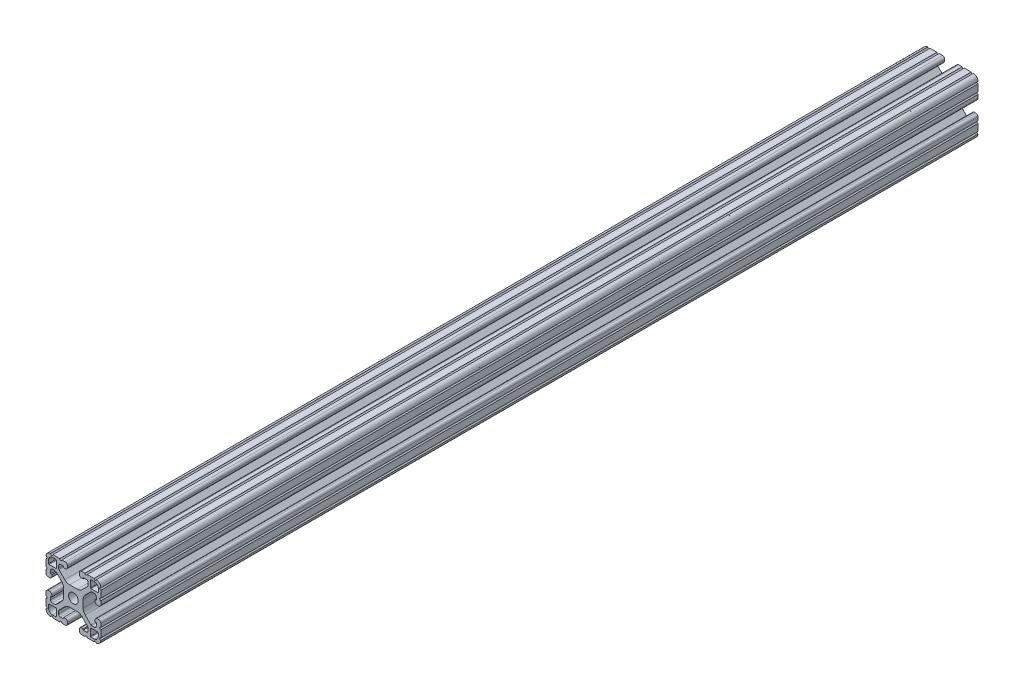
SolidWorks part; units mm, degrees
ref_plane "Front Plane" through (0, 0, 0) normal (0, 0, 1) x (1, 0, 0)
ref_plane "Top Plane" through (0, 0, 0) normal (0, 1, 0) x (1, 0, 0)
ref_plane "Right Plane" through (0, 0, 0) normal (1, 0, 0) x (0, 0, -1)
sketch "Sketch1" plane through (0, 0, 0) normal (0, 0, 1) x (1, 0, 0)
  line L0 (-10.0267, 12.1519) -> (-6.0215, 8.1473)
  line L1 (10.0267, -12.1519) -> (6.0215, -8.1473)
  line L2 (10.287, -14.5547) -> (10.287, -12.7802)
  line L3 (6.8141, -15.8247) -> (9.017, -15.8247)
  line L4 (-10.287, 14.5547) -> (-10.287, 12.7802)
  line L5 (6.8141, -14.986) -> (6.8141, -15.8247)
  line L6 (-6.8141, 15.8247) -> (-9.017, 15.8247)
  line L7 (2.6631, 6.7564) -> (-2.6631, 6.7564)
  line L8 (-6.8141, 14.986) -> (-6.8141, 15.8247)
  line L9 (-5.6388, 14.986) -> (-6.8141, 14.986)
  line L10 (-4.064, 17.4752) -> (-4.064, 16.5608)
  line L11 (-7.9756, 19.05) -> (-5.6388, 19.05)
  line L12 (-14.3256, 19.05) -> (-9.4996, 19.05)
  line L13 (-15.875, 19.05) -> (-15.8496, 19.05)
  line L14 (-19.05, 15.8496) -> (-19.05, 15.875)
  line L15 (-19.05, 9.4996) -> (-19.05, 14.3256)
  line L16 (-19.05, 5.6388) -> (-19.05, 7.9756)
  line L17 (5.6388, -14.986) -> (6.8141, -14.986)
  line L18 (4.064, -17.4752) -> (4.064, -16.5608)
  line L19 (7.9756, -19.05) -> (5.6388, -19.05)
  line L20 (-16.5608, 4.064) -> (-17.4752, 4.064)
  line L21 (14.3256, -19.05) -> (9.4996, -19.05)
  line L22 (-14.986, 6.7506) -> (-14.986, 5.6388)
  line L23 (-15.879, 6.7506) -> (-14.986, 6.7506)
  line L24 (15.875, -19.05) -> (15.8496, -19.05)
  line L25 (19.05, -15.8496) -> (19.05, -15.875)
  line L26 (-15.879, 8.9192) -> (-15.879, 6.7506)
  line L27 (-12.7428, 10.1892) -> (-14.609, 10.1892)
  line L28 (19.05, -9.4996) -> (19.05, -14.3256)
  line L29 (19.05, -5.6388) -> (19.05, -7.9756)
  line L30 (-8.1479, 5.9632) -> (-12.1142, 9.9289)
  line L31 (-16.891, 11.8618) -> (-12.2428, 11.8618)
  line L32 (-11.8618, 12.2428) -> (-11.8618, 16.891)
  line L33 (-12.2428, 17.272) -> (-14.478, 17.272)
  line L34 (-17.272, -14.478) -> (-17.272, -12.2428)
  line L35 (-12.2428, -17.272) -> (-14.478, -17.272)
  line L36 (-11.8618, -12.2428) -> (-11.8618, -16.891)
  line L37 (-16.891, -11.8618) -> (-12.2428, -11.8618)
  line L38 (-17.272, 14.478) -> (-17.272, 12.2428)
  line L39 (16.5608, -4.064) -> (17.4752, -4.064)
  line L40 (14.986, -6.7506) -> (14.986, -5.6388)
  line L41 (15.879, -6.7506) -> (14.986, -6.7506)
  line L42 (15.879, -8.9192) -> (15.879, -6.7506)
  line L43 (12.7428, -10.1892) -> (14.609, -10.1892)
  line L44 (8.1479, -5.9632) -> (12.1142, -9.9289)
  line L45 (6.7564, 2.6043) -> (6.7564, -2.6043)
  line L46 (17.272, 14.478) -> (17.272, 12.2428)
  line L47 (16.891, -11.8618) -> (12.2428, -11.8618)
  line L48 (11.8618, -12.2428) -> (11.8618, -16.891)
  line L49 (12.2428, -17.272) -> (14.478, -17.272)
  line L50 (17.272, -14.478) -> (17.272, -12.2428)
  line L51 (12.2428, 17.272) -> (14.478, 17.272)
  line L52 (11.8618, 12.2428) -> (11.8618, 16.891)
  line L53 (16.891, 11.8618) -> (12.2428, 11.8618)
  line L54 (8.1479, 5.9632) -> (12.1142, 9.9289)
  line L55 (12.7428, 10.1892) -> (14.609, 10.1892)
  line L56 (15.879, 8.9192) -> (15.879, 6.7506)
  line L57 (15.879, 6.7506) -> (14.986, 6.7506)
  line L58 (14.986, 6.7506) -> (14.986, 5.6388)
  line L59 (16.5608, 4.064) -> (17.4752, 4.064)
  line L60 (19.05, 5.6388) -> (19.05, 7.9756)
  line L61 (19.05, 9.4996) -> (19.05, 14.3256)
  line L62 (19.05, 15.8496) -> (19.05, 15.875)
  line L63 (15.875, 19.05) -> (15.8496, 19.05)
  line L64 (14.3256, 19.05) -> (9.4996, 19.05)
  line L65 (7.9756, 19.05) -> (5.6388, 19.05)
  line L66 (4.064, 17.4752) -> (4.064, 16.5608)
  line L67 (5.6388, 14.986) -> (6.8141, 14.986)
  line L68 (6.8141, 14.986) -> (6.8141, 15.8247)
  line L69 (6.8141, 15.8247) -> (9.017, 15.8247)
  line L70 (10.287, 14.5547) -> (10.287, 12.7802)
  line L71 (10.0267, 12.1519) -> (6.0215, 8.1473)
  line L72 (-6.7564, 2.6043) -> (-6.7564, -2.6043)
  line L73 (-8.1479, -5.9632) -> (-12.1142, -9.9289)
  line L74 (-12.7428, -10.1892) -> (-14.609, -10.1892)
  line L75 (-15.879, -8.9192) -> (-15.879, -6.7506)
  line L76 (-15.879, -6.7506) -> (-14.986, -6.7506)
  line L77 (-14.986, -6.7506) -> (-14.986, -5.6388)
  line L78 (-16.5608, -4.064) -> (-17.4752, -4.064)
  line L79 (-19.05, -5.6388) -> (-19.05, -7.9756)
  line L80 (-19.05, -9.4996) -> (-19.05, -14.3256)
  line L81 (-19.05, -15.8496) -> (-19.05, -15.875)
  line L82 (-15.875, -19.05) -> (-15.8496, -19.05)
  line L83 (-14.3256, -19.05) -> (-9.4996, -19.05)
  line L84 (-7.9756, -19.05) -> (-5.6388, -19.05)
  line L85 (-4.064, -17.4752) -> (-4.064, -16.5608)
  line L86 (-5.6388, -14.986) -> (-6.8141, -14.986)
  line L87 (-6.8141, -14.986) -> (-6.8141, -15.8247)
  line L88 (-6.8141, -15.8247) -> (-9.017, -15.8247)
  line L89 (-10.287, -14.5547) -> (-10.287, -12.7802)
  line L90 (-10.0267, -12.1519) -> (-6.0215, -8.1473)
  line L91 (-2.6631, -6.7564) -> (2.6631, -6.7564)
  arc A0 (-10.0267, 12.1519) -> (-10.287, 12.7802) centre (-9.3985, 12.7802) cw
  arc A1 (-19.05, -15.875) -> (-15.875, -19.05) centre (-15.875, -15.875) ccw construction
  arc A2 (-10.287, 14.5547) -> (-9.017, 15.8247) centre (-9.017, 14.5547) cw
  arc A3 (-4.064, 16.5608) -> (-5.6388, 14.986) centre (-5.6388, 16.5608) cw
  arc A4 (10.0267, -12.1519) -> (10.287, -12.7802) centre (9.3985, -12.7802) cw
  arc A5 (10.287, -14.5547) -> (9.017, -15.8247) centre (9.017, -14.5547) cw
  arc A6 (-5.6388, 19.05) -> (-4.064, 17.4752) centre (-5.6388, 17.4752) cw
  arc A7 (-7.9756, 19.05) -> (-9.4996, 19.05) centre (-8.7376, 19.05) cw
  arc A8 (-17.272, -14.478) -> (-14.478, -17.272) centre (-14.478, -14.478) ccw construction
  arc A9 (4.064, -16.5608) -> (5.6388, -14.986) centre (5.6388, -16.5608) cw
  arc A10 (-14.3256, 19.05) -> (-15.8496, 19.05) centre (-15.0876, 19.05) cw
  arc A11 (-19.05, 15.875) -> (-15.875, 19.05) centre (-15.875, 15.875) cw
  arc A12 (-6.0215, 8.1473) -> (-2.6631, 6.7564) centre (-2.6631, 11.5062) ccw
  arc A13 (6.0215, 8.1473) -> (2.6631, 6.7564) centre (2.6631, 11.5062) cw
  arc A14 (-19.05, 15.8496) -> (-19.05, 14.3256) centre (-19.05, 15.0876) cw
  arc A15 (-19.05, 9.4996) -> (-19.05, 7.9756) centre (-19.05, 8.7376) cw
  arc A16 (-17.4752, 4.064) -> (-19.05, 5.6388) centre (-17.4752, 5.6388) cw
  arc A17 (-14.986, 5.6388) -> (-16.5608, 4.064) centre (-16.5608, 5.6388) cw
  arc A18 (-15.879, 8.9192) -> (-14.609, 10.1892) centre (-14.609, 8.9192) cw
  arc A19 (-12.7428, 10.1892) -> (-12.1142, 9.9289) centre (-12.7428, 9.3002) cw
  arc A20 (-16.891, 11.8618) -> (-17.272, 12.2428) centre (-16.891, 12.2428) cw
  arc A21 (5.6388, -19.05) -> (4.064, -17.4752) centre (5.6388, -17.4752) cw
  arc A22 (7.9756, -19.05) -> (9.4996, -19.05) centre (8.7376, -19.05) cw
  arc A23 (14.3256, -19.05) -> (15.8496, -19.05) centre (15.0876, -19.05) cw
  arc A24 (-11.8618, 12.2428) -> (-12.2428, 11.8618) centre (-12.2428, 12.2428) cw
  arc A25 (19.05, -15.875) -> (15.875, -19.05) centre (15.875, -15.875) cw
  arc A26 (-12.2428, 17.272) -> (-11.8618, 16.891) centre (-12.2428, 16.891) cw
  arc A27 (-17.272, 14.478) -> (-14.478, 17.272) centre (-14.478, 14.478) cw
  arc A28 (19.05, -15.8496) -> (19.05, -14.3256) centre (19.05, -15.0876) cw
  arc A29 (19.05, -9.4996) -> (19.05, -7.9756) centre (19.05, -8.7376) cw
  arc A30 (17.4752, -4.064) -> (19.05, -5.6388) centre (17.4752, -5.6388) cw
  arc A31 (14.986, -5.6388) -> (16.5608, -4.064) centre (16.5608, -5.6388) cw
  arc A32 (15.879, -8.9192) -> (14.609, -10.1892) centre (14.609, -8.9192) cw
  arc A33 (12.7428, -10.1892) -> (12.1142, -9.9289) centre (12.7428, -9.3002) cw
  arc A34 (8.1479, -5.9632) -> (6.7564, -2.6043) centre (11.5062, -2.6043) cw
  arc A35 (6.7564, 2.6043) -> (8.1479, 5.9632) centre (11.5062, 2.6043) cw
  arc A36 (16.891, -11.8618) -> (17.272, -12.2428) centre (16.891, -12.2428) cw
  arc A37 (11.8618, -12.2428) -> (12.2428, -11.8618) centre (12.2428, -12.2428) cw
  arc A38 (-17.272, -14.478) -> (-14.478, -17.272) centre (-14.478, -14.478) ccw
  arc A39 (-12.2428, -17.272) -> (-11.8618, -16.891) centre (-12.2428, -16.891) ccw
  arc A40 (-11.8618, -12.2428) -> (-12.2428, -11.8618) centre (-12.2428, -12.2428) ccw
  arc A41 (-16.891, -11.8618) -> (-17.272, -12.2428) centre (-16.891, -12.2428) ccw
  arc A42 (12.2428, -17.272) -> (11.8618, -16.891) centre (12.2428, -16.891) cw
  circle A43 centre (0, 0) radius 3.3274
  arc A44 (17.272, -14.478) -> (14.478, -17.272) centre (14.478, -14.478) cw
  arc A45 (17.272, 14.478) -> (14.478, 17.272) centre (14.478, 14.478) ccw
  arc A46 (12.2428, 17.272) -> (11.8618, 16.891) centre (12.2428, 16.891) ccw
  arc A47 (11.8618, 12.2428) -> (12.2428, 11.8618) centre (12.2428, 12.2428) ccw
  arc A48 (16.891, 11.8618) -> (17.272, 12.2428) centre (16.891, 12.2428) ccw
  arc A49 (12.7428, 10.1892) -> (12.1142, 9.9289) centre (12.7428, 9.3002) ccw
  arc A50 (15.879, 8.9192) -> (14.609, 10.1892) centre (14.609, 8.9192) ccw
  arc A51 (14.986, 5.6388) -> (16.5608, 4.064) centre (16.5608, 5.6388) ccw
  arc A52 (17.4752, 4.064) -> (19.05, 5.6388) centre (17.4752, 5.6388) ccw
  arc A53 (19.05, 9.4996) -> (19.05, 7.9756) centre (19.05, 8.7376) ccw
  arc A54 (19.05, 15.8496) -> (19.05, 14.3256) centre (19.05, 15.0876) ccw
  arc A55 (19.05, 15.875) -> (15.875, 19.05) centre (15.875, 15.875) ccw
  arc A56 (14.3256, 19.05) -> (15.8496, 19.05) centre (15.0876, 19.05) ccw
  arc A57 (7.9756, 19.05) -> (9.4996, 19.05) centre (8.7376, 19.05) ccw
  arc A58 (5.6388, 19.05) -> (4.064, 17.4752) centre (5.6388, 17.4752) ccw
  arc A59 (4.064, 16.5608) -> (5.6388, 14.986) centre (5.6388, 16.5608) ccw
  arc A60 (10.287, 14.5547) -> (9.017, 15.8247) centre (9.017, 14.5547) ccw
  arc A61 (10.0267, 12.1519) -> (10.287, 12.7802) centre (9.3985, 12.7802) ccw
  arc A62 (-6.7564, 2.6043) -> (-8.1479, 5.9632) centre (-11.5062, 2.6043) ccw
  arc A63 (-8.1479, -5.9632) -> (-6.7564, -2.6043) centre (-11.5062, -2.6043) ccw
  arc A64 (-12.7428, -10.1892) -> (-12.1142, -9.9289) centre (-12.7428, -9.3002) ccw
  arc A65 (-15.879, -8.9192) -> (-14.609, -10.1892) centre (-14.609, -8.9192) ccw
  arc A66 (-14.986, -5.6388) -> (-16.5608, -4.064) centre (-16.5608, -5.6388) ccw
  arc A67 (-17.4752, -4.064) -> (-19.05, -5.6388) centre (-17.4752, -5.6388) ccw
  arc A68 (-19.05, -9.4996) -> (-19.05, -7.9756) centre (-19.05, -8.7376) ccw
  arc A69 (-19.05, -15.8496) -> (-19.05, -14.3256) centre (-19.05, -15.0876) ccw
  arc A70 (-19.05, -15.875) -> (-15.875, -19.05) centre (-15.875, -15.875) ccw
  arc A71 (-14.3256, -19.05) -> (-15.8496, -19.05) centre (-15.0876, -19.05) ccw
  arc A72 (-7.9756, -19.05) -> (-9.4996, -19.05) centre (-8.7376, -19.05) ccw
  arc A73 (-5.6388, -19.05) -> (-4.064, -17.4752) centre (-5.6388, -17.4752) ccw
  arc A74 (-4.064, -16.5608) -> (-5.6388, -14.986) centre (-5.6388, -16.5608) ccw
  arc A75 (-10.287, -14.5547) -> (-9.017, -15.8247) centre (-9.017, -14.5547) ccw
  arc A76 (-10.0267, -12.1519) -> (-10.287, -12.7802) centre (-9.3985, -12.7802) ccw
  arc A77 (-2.6631, -6.7564) -> (-6.0215, -8.1473) centre (-2.6631, -11.5062) ccw
  arc A78 (6.0215, -8.1473) -> (2.6631, -6.7564) centre (2.6631, -11.5062) ccw
  point P134 (0, 0)
extrude "Boss-Extrude1" add sketch "Sketch1" along normal mid plane 609.6
